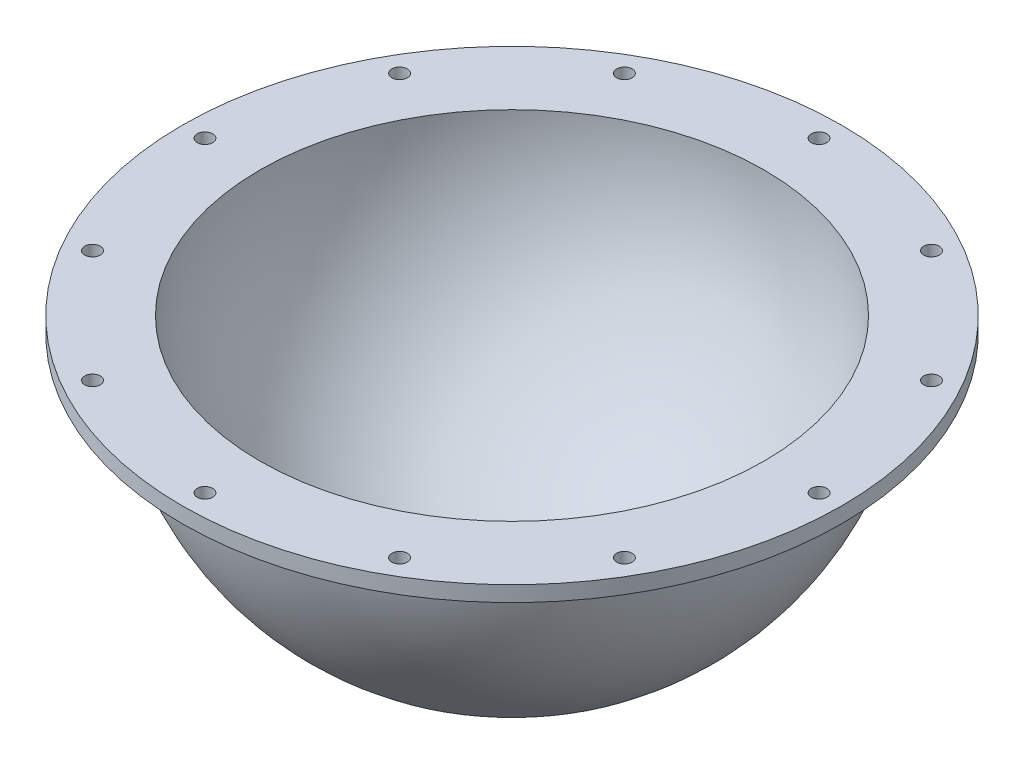
SolidWorks part; units mm, degrees
ref_plane "Front Plane" through (0, 0, 0) normal (0, 0, 1) x (1, 0, 0)
ref_plane "Top Plane" through (0, 0, 0) normal (0, 1, 0) x (1, 0, 0)
ref_plane "Right Plane" through (0, 0, 0) normal (1, 0, 0) x (0, 0, -1)
sketch "Sketch1" plane through (0, 0, 0) normal (0, 1, 0) x (1, 0, 0)
  line L0 (0, 220) -> (0, 195)
  line L1 (0, -195) -> (0, -220)
  line L2 (0, 220) -> (0, -220) construction
  arc A0 (0, 220) -> (0, -220) centre (0, 0) ccw
  arc A1 (0, 195) -> (0, -195) centre (0, 0) ccw
  dimension "D1" = 220
  dimension "D2" = 25
revolve "Revolve1" add sketch "Sketch1" angle 180 about L2
ref_axis "Axis1" through (0, 0, 0) along (0, 1, 0)
sketch "Sketch3" plane through (0, 0, 0) normal (1, 0, 0) x (0, 0, -1)
  line L0 (-220, 0) -> (-255, 0)
  line L1 (-255, 0) -> (-255, -12)
  line L2 (-255, -12) -> (-219.6725, -12)
  line L3 (-255, 0) -> (255, 0) construction
  arc A0 (-220, 0) -> (220, 0) centre (0, 0) ccw construction
  arc A1 (-220, 0) -> (-219.6725, -12) centre (0, 0) ccw
  point P10 (-237.5, 0)
  dimension "D1" = 510
  dimension "D2" = 12
revolve "Revolve2" add sketch "Sketch3" angle 360 about axis through (0, 0, 0) along (0, 1, 0)
sketch "Sketch10" plane through (0, 0, 0) normal (0, 1, 0) x (1, 0, 0)
  circle A0 centre (0, 0) radius 237.5 construction
  circle A1 centre (0, 237.5) radius 6
  circle A2 centre (-118.75, 205.681) radius 6
  circle A3 centre (-205.681, 118.75) radius 6
  circle A4 centre (-237.5, 0) radius 6
  circle A5 centre (-205.681, -118.75) radius 6
  circle A6 centre (-118.75, -205.681) radius 6
  circle A7 centre (0, -237.5) radius 6
  circle A8 centre (118.75, -205.681) radius 6
  circle A9 centre (205.681, -118.75) radius 6
  circle A10 centre (237.5, 0) radius 6
  circle A11 centre (205.681, 118.75) radius 6
  circle A12 centre (118.75, 205.681) radius 6
  point P30 (0, 0)
  dimension "D1" = 475
  dimension "D2" = 12
  dimension "D3" = 12
extrude "Cut-Extrude1" cut sketch "Sketch10" against normal through all
equation "\"mbtOD\" = 500"
equation "\"mbtT\" = 6"
equation "\"mbtL\" = 3000"
equation "\"mbtFlangeOD\" = 650"
equation "\"mbtFlangeT\" = 12"
equation "\"mbtFlangeBoltCircleDia\" = 650"
equation "\"mbtFlangeHoleDia\" = 12"
equation "\"mbtOringSize\" = 10 "
equation "\"mbtOringDia\" = 620"
equation "\"mbtWidth\" = 2250"
equation "\"skiWidth\" = 1250"
equation "\"mbtCapL\" = 500"
equation "\"vbtRearOD\" = 800"
equation "\"vbtRearT\" = 6.25"
equation "\"vbtRearFlangeOD\" = 900"
equation "\"vbtRearFlangeT\" = 12"
equation "\"vbtRearBoltHoleDia\" = 12"
equation "\"vbtFrontOD\" = 440"
equation "\"vbtFrontT\" = 25"
equation "\"vbtFrontFlangeOD\" = 510"
equation "\"vbtFrontFlangeT\" = 12"
equation "\"vbtFrontBoltHoleDia\" = 12"
equation "\"D1@Sketch1\"=\"vbtFrontOD\"/2"
equation "\"D2@Sketch1\"=\"vbtFrontT\""
equation "\"D1@Sketch3\"=\"vbtFrontFlangeOD\""
equation "\"D2@Sketch3\"=\"vbtFrontFlangeT\""
equation "\"D1@Sketch10\"=(\"vbtFrontOD\"+\"vbtFrontFlangeOD\")/2"
equation "\"D2@Sketch10\"=\"vbtFrontBoltHoleDia\""
